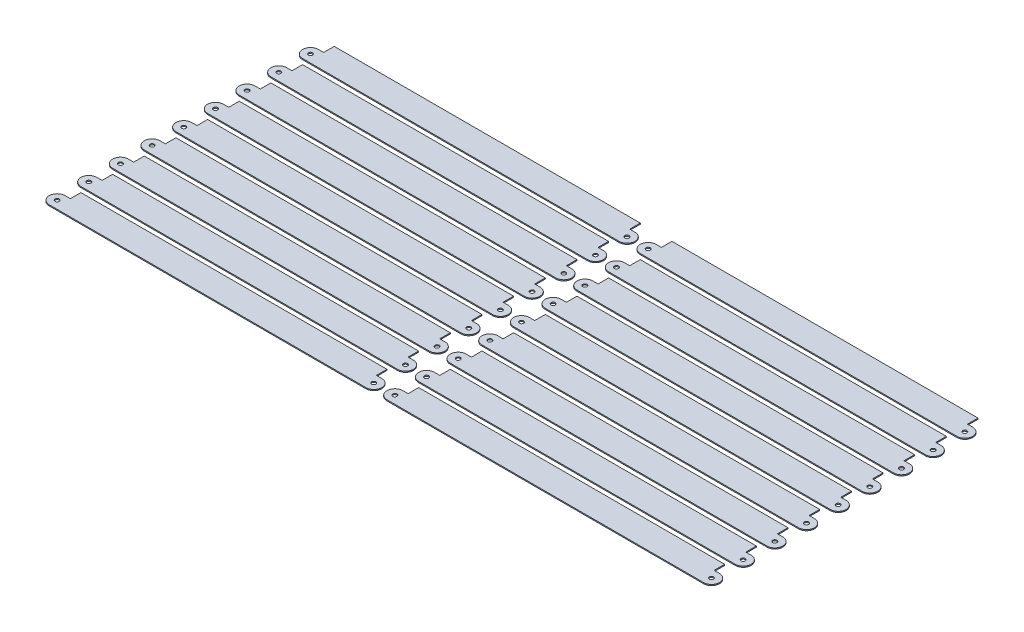
SolidWorks part; units mm, degrees
ref_plane "Front Plane" through (0, 0, 0) normal (0, 0, 1) x (1, 0, 0)
ref_plane "Top Plane" through (0, 0, 0) normal (0, 1, 0) x (1, 0, 0)
ref_plane "Right Plane" through (0, 0, 0) normal (1, 0, 0) x (0, 0, -1)
sketch "Sketch1" plane through (0, 0, 0) normal (0, 1, 0) x (1, 0, 0)
  line L0 (0, 0) -> (300, 0) construction
  line L1 (0, 7.5) -> (5, 7.5)
  line L2 (0, 7.5) -> (300, 7.5) construction
  line L3 (0, 7.5) -> (0, -7.5) construction
  line L4 (0, -7.5) -> (300, -7.5)
  line L5 (300, 7.5) -> (300, -7.5) construction
  line L6 (0, 7.5) -> (300, -7.5) construction
  line L7 (0, -7.5) -> (300, 7.5) construction
  line L8 (5, 7.5) -> (5, 17.5)
  line L9 (5, 17.5) -> (295, 17.5)
  line L10 (295, 17.5) -> (295, 7.5)
  line L11 (295, 7.5) -> (300, 7.5)
  line L12 (150, 0) -> (150, 17.5) construction
  line L17 (300, 0) -> (307.5, 0) construction
  line L19 (307.5, 1) -> (307.5, -1)
  line L20 (307.5, 1) -> (307.433, 1)
  line L21 (307.5, -1) -> (307.433, -1)
  line L32 (-7.5, 1) -> (-7.5, -1)
  line L33 (-7.5, -1) -> (-7.433, -1)
  line L44 (-7.5, 1) -> (-7.433, 1)
  circle A0 centre (0, 0) radius 2
  circle A1 centre (300, 0) radius 2
  arc A2 (0, 7.5) -> (0, -7.5) centre (0, 0) ccw construction
  arc A3 (300, -7.5) -> (300, 7.5) centre (300, 0) ccw construction
  arc A96 (0, 7.5) -> (-7.433, 1) centre (0, 0) ccw
  arc A97 (-7.433, -1) -> (0, -7.5) centre (0, 0) ccw
  arc A98 (307.433, 1) -> (300, 7.5) centre (300, 0) ccw
  arc A99 (307.433, -1) -> (300, -7.5) centre (300, 0) cw
  point P5 (150, 0)
  point P15 (-7.5, 0)
  dimension "D3" = 10
  dimension "D5" = 4
  dimension "D7" = 2
  dimension "D1" = 2
  dimension "D2" = 5
  dimension "D4" = 15
  dimension "D6" = 300
extrude "Boss-Extrude1" add sketch "Sketch1" along normal blind 1
pattern_linear "LPattern1" count 9 spacing 30 along (0, 0, -1) count 2 spacing 320 along (1, 0, 0) of bodies 101
